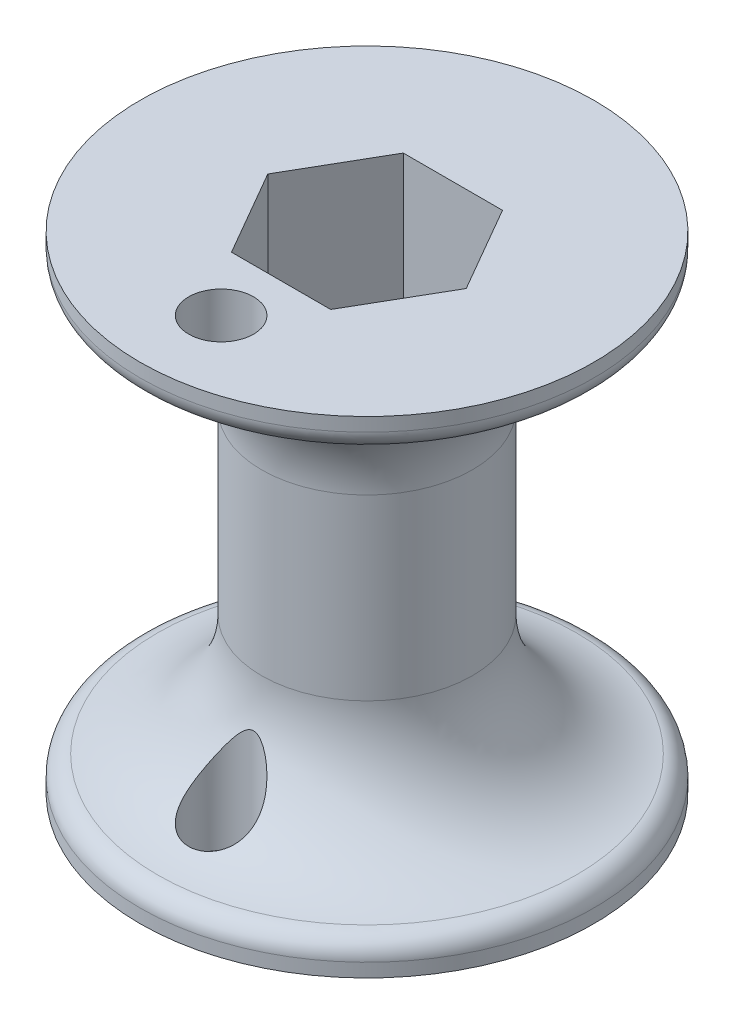
SolidWorks part; units mm, degrees
ref_plane "Front Plane" through (0, 0, 0) normal (0, 0, 1) x (1, 0, 0)
ref_plane "Top Plane" through (0, 0, 0) normal (0, 1, 0) x (1, 0, 0)
ref_plane "Right Plane" through (0, 0, 0) normal (1, 0, 0) x (0, 0, -1)
sketch "Sketch1" plane through (0, 0, 0) normal (1, 0, 0) x (0, 0, -1)
  line L0 (0, 0) -> (0, 19.05)
  line L1 (0, 19.05) -> (17.78, 19.05)
  line L2 (17.78, 19.05) -> (17.78, 16.51)
  line L4 (8.255, 6.985) -> (8.255, 0)
  line L5 (8.255, 0) -> (0, 0)
  arc A0 (8.255, 6.985) -> (17.78, 16.51) centre (17.78, 6.985) cw
  point P8 (0, 0)
  point P9 (0, 0)
  dimension "D1" = 19.05
  dimension "D3" = 2.54
  dimension "D4" = 8.255
  dimension "D5" = 17.78
  dimension "D6" = 6.985
revolve "Revolve1" add sketch "Sketch1" angle 360 about L0
mirror "Mirror1" about plane through (0, 0, -8.255) normal (0, -1, 0) of "Revolve1"
sketch "Sketch2" plane through (0, 19.05, 0) normal (0, 1, 0) x (1, 0, 0)
  line L7 (-3.8861, -6.731) -> (3.8861, -6.731)
  line L8 (3.8861, -6.731) -> (7.7723, 0)
  line L9 (7.7723, 0) -> (3.8861, 6.731)
  line L10 (3.8861, 6.731) -> (-3.8861, 6.731)
  line L11 (-3.8861, 6.731) -> (-7.7723, 0)
  line L12 (-7.7723, 0) -> (-3.8861, -6.731)
  circle A0 centre (0, 0) radius 6.731 construction
  circle A1 centre (0, -11.43) radius 2.54
  circle A2 centre (0, 0) radius 17.78 construction
  dimension "D2" = 5.08
  dimension "D1" = 13.462
  dimension "." = 11.43
extrude "Cut-Extrude1" cut sketch "Sketch2" against normal through all
fillet "Fillet1" radius 1.5875 2 edges at (0, 16.51, -17.78) (0, -16.51, -17.78)
